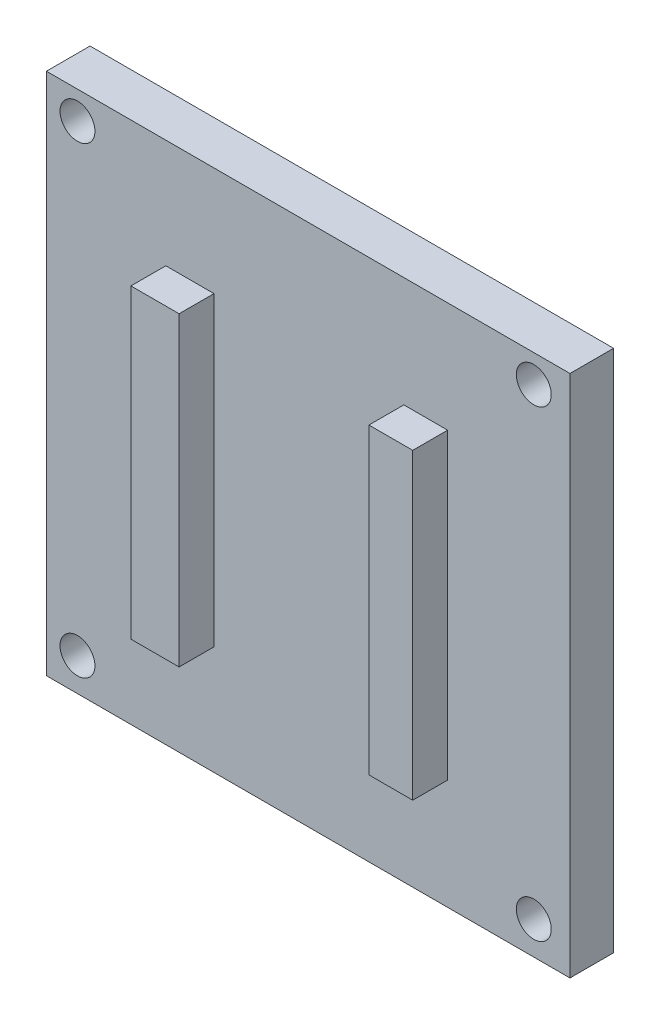
SolidWorks part; units mm, degrees
ref_plane "Front Plane" through (0, 0, 0) normal (0, 0, 1) x (1, 0, 0)
ref_plane "Top Plane" through (0, 0, 0) normal (0, 1, 0) x (1, 0, 0)
ref_plane "Right Plane" through (0, 0, 0) normal (1, 0, 0) x (0, 0, -1)
sketch "Sketch1" plane through (0, 0, 0) normal (0, 0, 1) x (1, 0, 0)
  line L1 (-30, -30) -> (30, -30)
  line L2 (-30, -30) -> (-30, 30)
  line L3 (-30, 30) -> (30, 30)
  line L4 (30, -30) -> (30, 30)
  line L5 (-30, -30) -> (30, 30) construction
  line L6 (-30, 30) -> (30, -30) construction
  point P0 (0, 0)
  dimension "D1" = 60
  dimension "D2" = 60
extrude "Boss-Extrude1" add sketch "Sketch1" against normal blind 5
sketch "Sketch2" plane through (0, 0, 0) normal (0, 0, 1) x (1, 0, 0)
  circle A0 centre (-26.441, 26.8175) radius 2
  dimension "D1" = 4
extrude "Cut-Extrude1" cut sketch "Sketch2" against normal through all
sketch "Sketch5" plane through (0, 0, 0) normal (0, 0, 1) x (1, 0, 0)
  circle A0 centre (-26.441, -26.2318) radius 2
  dimension "D1" = 4
extrude "Cut-Extrude2" cut sketch "Sketch5" against normal through all
sketch "Sketch6" plane through (0, 0, 0) normal (0, 0, 1) x (1, 0, 0)
  circle A0 centre (25.8553, 26.8175) radius 2
  dimension "D1" = 4
extrude "Cut-Extrude3" cut sketch "Sketch6" against normal through all contours A0
sketch "Sketch7" plane through (0, 0, 0) normal (0, 0, 1) x (1, 0, 0)
  circle A0 centre (25.8553, -26.2318) radius 2
  dimension "D1" = 4
extrude "Cut-Extrude4" cut sketch "Sketch7" against normal through all
sketch "Sketch8" plane through (0, 0, 0) normal (0, 0, 1) x (1, 0, 0)
  line L1 (-16.3164, 17.5297) -> (-10.794, 17.5297)
  line L2 (-16.3164, 17.5297) -> (-16.3164, -17.5297)
  line L3 (-16.3164, -17.5297) -> (-10.794, -17.5297)
  line L4 (-10.794, 17.5297) -> (-10.794, -17.5297)
  line L5 (-16.3164, 17.5297) -> (-10.794, -17.5297) construction
  line L6 (-16.3164, -17.5297) -> (-10.794, 17.5297) construction
  point P0 (-13.5552, 0)
extrude "Boss-Extrude2" add sketch "Sketch8" along normal blind 4
sketch "Sketch11" plane through (0, 0, 0) normal (0, 0, 1) x (1, 0, 0)
  line L1 (10.9613, 17.3624) -> (15.9817, 17.3624)
  line L2 (10.9613, 17.3624) -> (10.9613, -17.3624)
  line L3 (10.9613, -17.3624) -> (15.9817, -17.3624)
  line L4 (15.9817, 17.3624) -> (15.9817, -17.3624)
  line L5 (10.9613, 17.3624) -> (15.9817, -17.3624) construction
  line L6 (10.9613, -17.3624) -> (15.9817, 17.3624) construction
  point P0 (13.4715, 0)
extrude "Boss-Extrude3" add sketch "Sketch11" along normal blind 4
